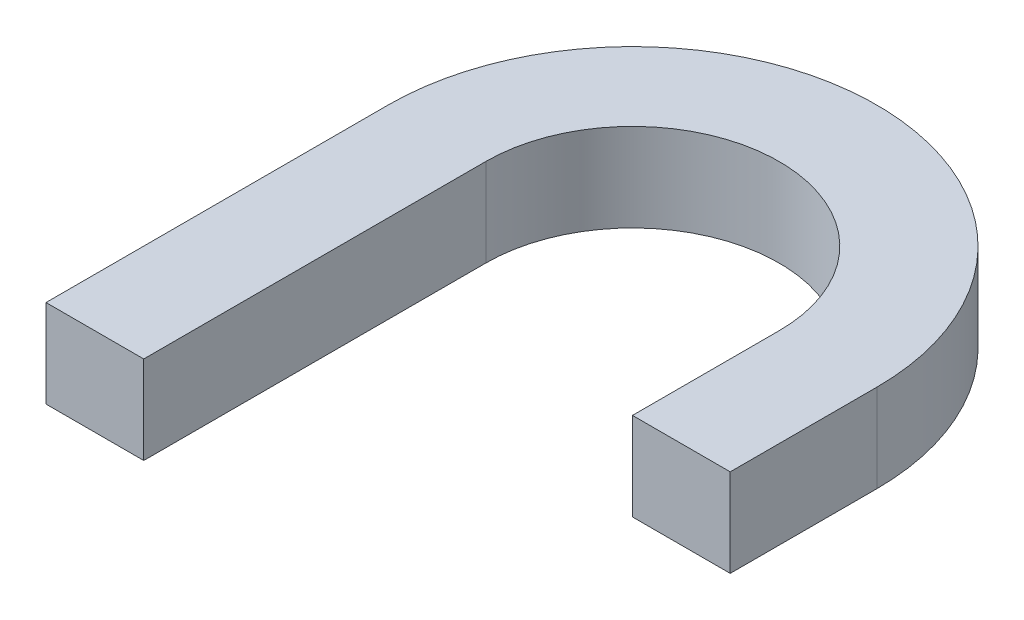
SolidWorks part; units mm, degrees
ref_plane "Front Plane" through (0, 0, 0) normal (0, 0, 1) x (1, 0, 0)
ref_plane "Top Plane" through (0, 0, 0) normal (0, 1, 0) x (1, 0, 0)
ref_plane "Right Plane" through (0, 0, 0) normal (1, 0, 0) x (0, 0, -1)
sketch "Sketch1" plane through (0, 0, 0) normal (0, 1, 0) x (1, 0, 0)
  line L3 (-63.5, 0) -> (-63.5, -88.9)
  line L12 (63.5, -38.1) -> (63.5, 0)
  line L16 (-38.1, 0) -> (-38.1, -88.9)
  line L21 (38.1, -38.1) -> (38.1, 0)
  line L26 (-60.7762, -86.3911) -> (-38.1, -88.2572) construction
  line L27 (-60.7762, 0) -> (-60.7762, -86.3911) construction
  line L28 (-38.1, 0) -> (-38.1, -88.2572) construction
  line L29 (38.1, -131.6846) -> (38.1, 0) construction
  line L30 (60.7762, -37.7758) -> (38.1, -131.6846) construction
  line L31 (60.7762, -37.7758) -> (60.7762, 0) construction
  line L32 (-35.3762, 0) -> (-35.3762, -91.2143) construction
  line L33 (35.3762, -154.5689) -> (35.3762, 0) construction
  line L34 (63.5, -38.1) -> (35.3762, -154.5689) construction
  line L35 (38.1, -38.1) -> (63.5, -38.1)
  line L36 (-63.5, -88.9) -> (-35.3762, -91.2143) construction
  line L37 (-63.5, -88.9) -> (-38.1, -88.9)
  arc A4 (63.5, 0) -> (-63.5, 0) centre (0, 0) ccw
  arc A5 (38.1, 0) -> (-38.1, 0) centre (0, 0) ccw construction
  arc A7 (38.1, 0) -> (-38.1, 0) centre (0, 0) ccw
  arc A9 (60.7762, 0) -> (-60.7762, 0) centre (0, 0) ccw construction
  arc A10 (35.3762, 0) -> (-35.3762, 0) centre (0, 0) ccw construction
  dimension "D2" = 76.2
  dimension "D3" = 88.9
  dimension "D4" = 38.1
  dimension "D13" = 25.4
extrude "Boss-Extrude1" add sketch "Sketch1" along normal mid plane 22.86
